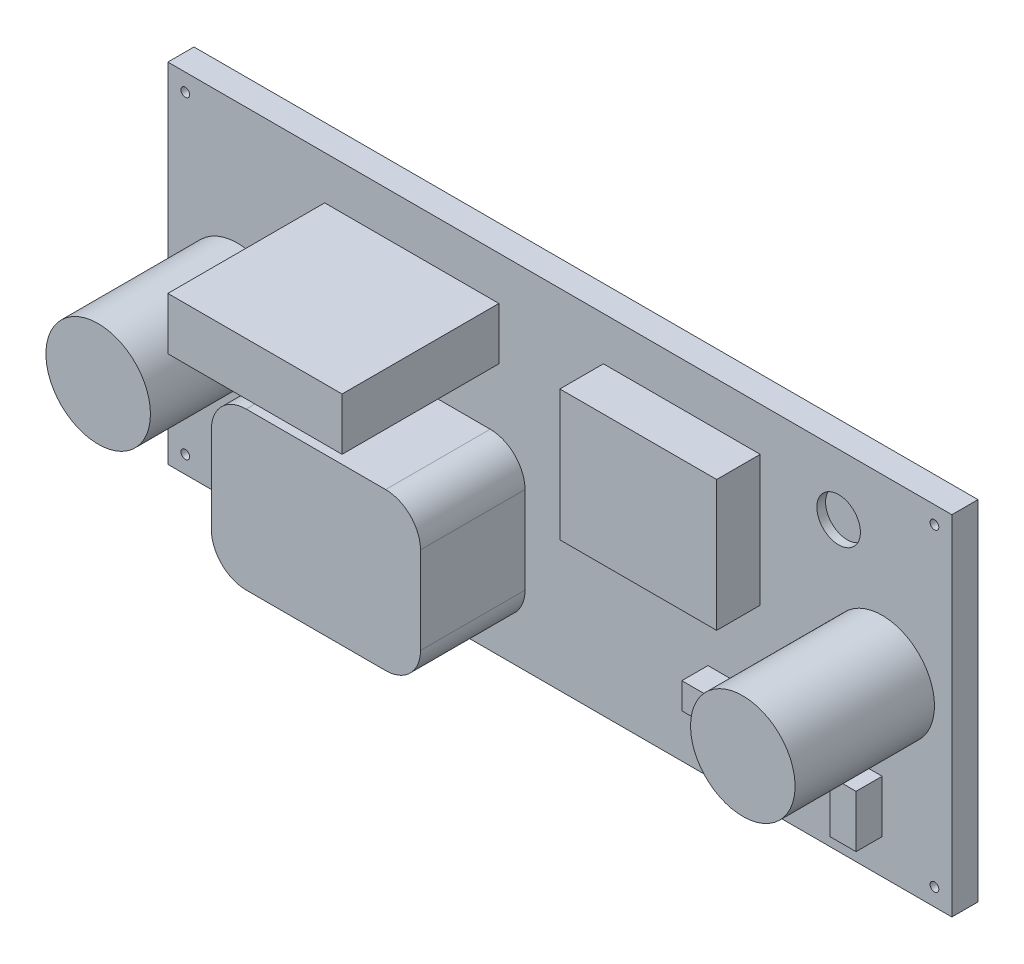
SolidWorks part; units mm, degrees
ref_plane "Front Plane" through (0, 0, 0) normal (0, 0, 1) x (1, 0, 0)
ref_plane "Top Plane" through (0, 0, 0) normal (0, 1, 0) x (1, 0, 0)
ref_plane "Right Plane" through (0, 0, 0) normal (1, 0, 0) x (0, 0, -1)
sketch "Sketch1" plane through (0, 0, 0) normal (0, 0, 1) x (1, 0, 0)
  line L1 (-22.5, 10) -> (22.5, 10)
  line L2 (-22.5, 10) -> (-22.5, -10)
  line L3 (-22.5, -10) -> (22.5, -10)
  line L4 (22.5, 10) -> (22.5, -10)
  line L5 (-22.5, 10) -> (22.5, -10) construction
  line L6 (-22.5, -10) -> (22.5, 10) construction
  point P0 (0, 0)
  dimension "D1" = 45
  dimension "D2" = 20
extrude "Boss-Extrude1" add sketch "Sketch1" along normal blind 1.5
sketch "Sketch2" plane through (0, 0, 1.5) normal (0, 0, 1) x (1, 0, 0)
  line L0 (-22.5, 10) -> (-22.5, -10) construction
  line L1 (-22.5, -10) -> (22.5, -10) construction
  line L2 (0, 9.2301) -> (0, -9.3624) construction
  circle A0 centre (-18.5, 0) radius 3
  circle A1 centre (18.5, 0) radius 3
  dimension "D2" = 6
  dimension "D1" = 4
  dimension "D3" = 10
extrude "Boss-Extrude3" add sketch "Sketch2" along normal blind 8
sketch "Sketch3" plane through (0, 0, 1.5) normal (0, 0, 1) x (1, 0, 0)
  line L0 (0, 9.0316) -> (0, -8.6346) construction
  line L1 (22.5, 10) -> (-22.5, 10) construction
  line L2 (-13.5, 7.5) -> (-3.5, 7.5)
  line L3 (-13.5, 7.5) -> (-13.5, 4.5)
  line L4 (-13.5, 4.5) -> (-3.5, 4.5)
  line L5 (-3.5, 7.5) -> (-3.5, 4.5)
  line L6 (-13.5, 7.5) -> (-3.5, 4.5) construction
  line L7 (-13.5, 4.5) -> (-3.5, 7.5) construction
  line L8 (-22.5, 10) -> (-22.5, -10) construction
  point P2 (-8.5, 6)
  dimension "D1" = 10
  dimension "D2" = 3
  dimension "D3" = 2.5
  dimension "D4" = 9
extrude "Boss-Extrude4" add sketch "Sketch3" along normal blind 9
sketch "Sketch5" plane through (0, 0, 1.5) normal (0, 0, 1) x (1, 0, 0)
  line L0 (-22.5, -10) -> (22.5, -10) construction
  line L1 (-12, 1) -> (-4, 1)
  line L2 (-14, -1) -> (-14, -6)
  line L3 (-12, -8) -> (-4, -8)
  line L4 (-2, -1) -> (-2, -6)
  line L5 (-14, 1) -> (-2, -8) construction
  line L6 (-14, -8) -> (-2, 1) construction
  line L7 (-22.5, 10) -> (-22.5, -10) construction
  arc A0 (-14, -6) -> (-12, -8) centre (-12, -6) ccw
  arc A1 (-4, -8) -> (-2, -6) centre (-4, -6) ccw
  arc A2 (-2, -1) -> (-4, 1) centre (-4, -1) ccw
  arc A3 (-12, 1) -> (-14, -1) centre (-12, -1) ccw
  point P0 (-8, -3.5)
  dimension "D5" = 2
  dimension "D1" = 12
  dimension "D2" = 9
  dimension "D3" = 2
  dimension "D4" = 8.5
extrude "Boss-Extrude5" add sketch "Sketch5" along normal blind 6
sketch "Sketch6" plane through (0, 0, 1.5) normal (0, 0, 1) x (1, 0, 0)
  line L0 (22.5, 10) -> (-22.5, 10) construction
  line L1 (2.5, 7.5) -> (11.5, 7.5)
  line L2 (2.5, 7.5) -> (2.5, 0)
  line L3 (2.5, 0) -> (11.5, 0)
  line L4 (11.5, 7.5) -> (11.5, 0)
  line L5 (2.5, 7.5) -> (11.5, 0) construction
  line L6 (2.5, 0) -> (11.5, 7.5) construction
  line L7 (22.5, -10) -> (22.5, 10) construction
  point P0 (7, 3.75)
  dimension "D1" = 7.5
  dimension "D2" = 2.5
  dimension "D3" = 9
  dimension "D4" = 11
extrude "Boss-Extrude6" add sketch "Sketch6" along normal blind 2.5
sketch "Sketch7" plane through (0, 0, 1.5) normal (0, 0, 1) x (1, 0, 0)
  line L0 (-22.5, -10) -> (22.5, -10) construction
  line L1 (17, -5) -> (18.5, -5)
  line L2 (17, -5) -> (17, -8)
  line L3 (17, -8) -> (18.5, -8)
  line L4 (18.5, -5) -> (18.5, -8)
  line L5 (17, -5) -> (18.5, -8) construction
  line L6 (17, -8) -> (18.5, -5) construction
  line L7 (8.5, -4.5) -> (11.5, -4.5)
  line L8 (8.5, -4.5) -> (8.5, -6)
  line L9 (8.5, -6) -> (11.5, -6)
  line L10 (11.5, -4.5) -> (11.5, -6)
  line L11 (8.5, -4.5) -> (11.5, -6) construction
  line L12 (8.5, -6) -> (11.5, -4.5) construction
  line L13 (22.5, -10) -> (22.5, 10) construction
  line L14 (22.5, 10) -> (-22.5, 10) construction
  point P0 (17.75, -6.5)
  point P5 (10, -5.25)
  dimension "D1" = 3
  dimension "D2" = 1.5
  dimension "D3" = 3
  dimension "D4" = 1.5
  dimension "D5" = 4
  dimension "D6" = 11
  dimension "D7" = 4
  dimension "D8" = 15
extrude "Boss-Extrude7" add sketch "Sketch7" along normal blind 1.5
sketch "Sketch9" plane through (0, 0, 1.5) normal (0, 0, 1) x (1, 0, 0)
  line L0 (-22.5, -10) -> (22.5, -10) construction
  line L1 (-22.5, 10) -> (-22.5, -10) construction
  circle A0 centre (-17.5, -7) radius 1.25
  dimension "D1" = 2.5
  dimension "D2" = 3
  dimension "D3" = 5
extrude "Cut-Extrude1" cut sketch "Sketch9" against normal blind 0.5
sketch "Sketch10" plane through (0, 0, 1.5) normal (0, 0, 1) x (1, 0, 0)
  line L0 (22.5, -10) -> (22.5, 10) construction
  line L1 (-22.5, -10) -> (22.5, -10) construction
  circle A0 centre (16, 6.5) radius 1.25
  dimension "D1" = 2.5
  dimension "D2" = 6.5
  dimension "D3" = 16.5
extrude "Cut-Extrude2" cut sketch "Sketch10" against normal blind 0.5
sketch "Sketch12" plane through (0, 0, 1.5) normal (0, 0, 1) x (1, 0, 0)
  line L0 (-22.5, 10) -> (-22.5, -10) construction
  line L1 (22.5, 10) -> (-22.5, 10) construction
  line L2 (22.5, -10) -> (22.5, 10) construction
  line L3 (-22.5, -10) -> (22.5, -10) construction
  circle A0 centre (-21.5, 9) radius 0.25
  circle A1 centre (21.5, 9) radius 0.25
  circle A2 centre (21.5, -9) radius 0.25
  circle A3 centre (-21.5, -9) radius 0.25
  dimension "D1" = 0.5
  dimension "D2" = 0.5
  dimension "D3" = 0.5
  dimension "D4" = 0.5
  dimension "D5" = 1
  dimension "D6" = 1
  dimension "D7" = 1
  dimension "D8" = 1
  dimension "D9" = 1
  dimension "D10" = 1
  dimension "D11" = 1
  dimension "D12" = 1
extrude "Cut-Extrude3" cut sketch "Sketch12" against normal blind 1.5
